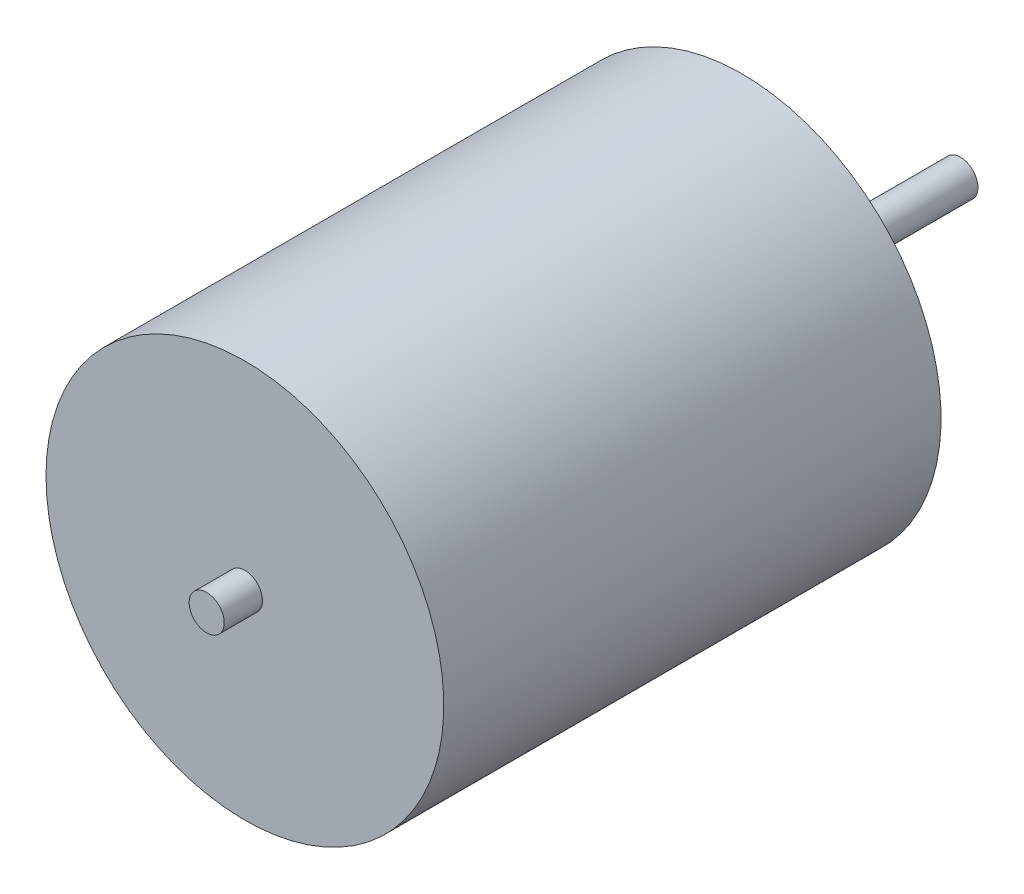
SolidWorks part; units mm, degrees
other "Camera1"
ref_plane "Front Plane" through (0, 0, 0) normal (0, 0, 1) x (1, 0, 0)
ref_plane "Top Plane" through (0, 0, 0) normal (0, 1, 0) x (1, 0, 0)
ref_plane "Right Plane" through (0, 0, 0) normal (1, 0, 0) x (0, 0, -1)
sketch "Sketch2" plane through (0, 0, 0) normal (0, 1, 0) x (1, 0, 0)
  line L0 (0, 54.9739) -> (0, -1.9337) construction
  line L1 (0, 0) -> (18, 0)
  line L2 (18, 0) -> (18, 45)
  line L3 (18, 45) -> (6.5, 45)
  line L4 (6.5, 45) -> (6.5, 50)
  line L5 (6.5, 50) -> (5.4551, 50)
  line L6 (5.4551, 50) -> (5.4551, 49.6)
  line L7 (5.4551, 49.6) -> (0, 49.6)
  line L8 (0, 0) -> (0, 49.6)
  dimension "D1" = 36
  dimension "D2" = 13
  dimension "D3" = 45
  dimension "D4" = 5
  dimension "D5" = 0.4
revolve "Revolve1" add sketch "Sketch2" angle 360 about L0
sketch "Sketch3" plane through (0, 0, 0) normal (0, 1, 0) x (1, 0, 0)
  line L0 (0, 0) -> (0, 78.936) construction
  line L1 (0, -3.4587) -> (0, 64.7595)
revolve "Revolve-Thin1" add sketch "Sketch3" angle 360 about L0 wall 1.5875
sketch "Sketch4" plane through (0, 0, 0) normal (0, 1, 0) x (1, 0, 0)
  line L4 (0, 43.5) -> (0, 1.5)
  line L8 (-16.5, 1.5) -> (16.5, 1.5)
  line L9 (16.5, 43.5) -> (-16.5, 43.5)
  line L10 (16.5, 1.5) -> (16.5, 43.5)
  line L11 (-16.5, 43.5) -> (-16.5, 1.5)
  line L12 (0, 1.5) -> (16.5, 1.5)
  line L13 (16.5, 43.5) -> (0, 43.5)
  line L14 (16.5, 1.5) -> (16.5, 43.5)
  dimension "D1" = 1.5
revolve "Cut-Revolve2" cut sketch "Sketch4" angle 360 about L0
sketch "Sketch5" plane through (0, 0, -45) normal (0, 0, -1) x (-1, 0, 0)
  line L0 (-20.5635, 0) -> (22.0219, 0) construction
  line L1 (0, -19.3603) -> (0, 19.2145) construction
  line L2 (0, 0) -> (15.3315, 15.3315) construction
  line L3 (0, 0) -> (-15.759, -15.759) construction
  line L4 (0, 0) -> (14.7022, -14.7022) construction
  arc A0 (-12.5, 0) -> (0, 12.5) centre (0, 0) cw construction
  arc A1 (0, 14) -> (-14, 0) centre (0, 0) ccw
  arc A2 (0, 11) -> (-11, 0) centre (0, 0) ccw
  arc A3 (0, 11) -> (0, 14) centre (0, 12.5) ccw
  arc A4 (-14, 0) -> (-11, 0) centre (-12.5, 0) ccw
  arc A5 (0, -12.5) -> (12.5, 0) centre (0, 0) ccw construction
  arc A6 (14, 0) -> (0, -14) centre (0, 0) cw
  arc A7 (11, 0) -> (0, -11) centre (0, 0) cw
  arc A8 (11, 0) -> (14, 0) centre (12.5, 0) cw
  arc A9 (0, -14) -> (0, -11) centre (0, -12.5) cw
  circle A10 centre (9.5459, 9.5459) radius 1.5
  circle A11 centre (-9.5459, -9.5459) radius 1.5
  point P4 (-8.8388, 8.8388)
  point P18 (8.8388, -8.8388)
  dimension "D1" = 12.5
  dimension "D2" = 1.5
  dimension "D5" = 3
  dimension "D3" = 45
  dimension "D4" = 45
  dimension "D6" = 27
extrude "Cut-Extrude1" cut sketch "Sketch5" against normal up to next
